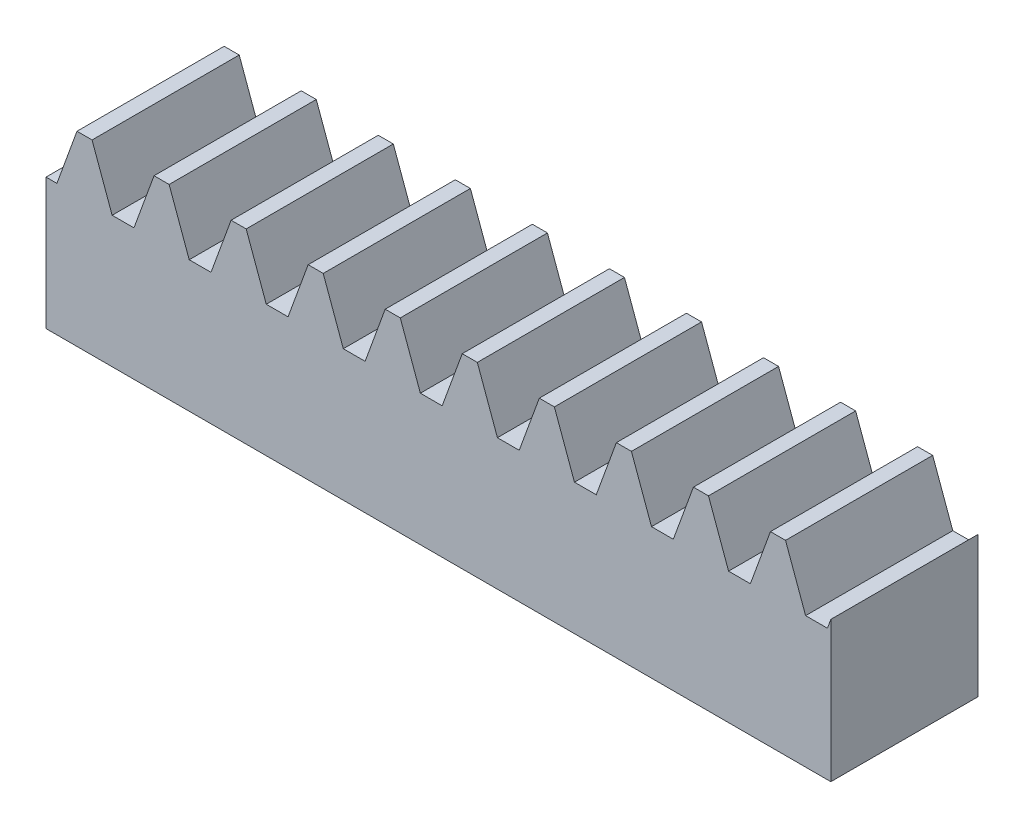
SolidWorks part; units mm, degrees
extrude "Blank" add sketch "BlankSke" against normal blind 3
sketch "BlankSke" plane through (0, 0, 0) normal (0, 0, 1) x (1, 0, 0)
  line L1 (0, 0) -> (16, 0)
  line L2 (0, 0) -> (0, 3.8)
  line L3 (0, 3.8) -> (16, 3.8)
  line L4 (16, 0) -> (16, 3.8)
  dimension "Length" = 16
  dimension "Blank_height" = 3.8
ref_plane "Plane1" through (0, 0, 0) normal (0, 0, 1) x (1, 0, 0)
ref_plane "Plane2" through (0, 0, 0) normal (0, 1, 0) x (1, 0, 0)
ref_plane "Plane3" through (0, 0, 0) normal (1, 0, 0) x (0, 0, -1)
other "Configuration Table"
sketch "HoldingSke" plane through (0, 0, 0) normal (0, 1, 0) x (1, 0, 0)
  line L0 (0, 0) -> (0.2783, 1.9805)
  line L1 (-15, 0) -> (100, 0) construction
  line L2 (0, 0) -> (-2.1039, 2.3779)
  line L3 (0, 0) -> (-11.863, 4.5341)
  line L4 (0, 0) -> (8.4473, 1.7955)
  line L5 (0, 0) -> (-23.7986, -8.8762)
  line L6 (0, 0) -> (-10.5278, -7.1032)
  line L9 (-71.009, 38.7566) -> (-55.9739, 44.2289)
  line L10 (-76.2, 2.8779) -> (-72.4, 2.8779)
  line L11 (0, 0) -> (-3, 0)
  line L12 (-76.2, 101.6) -> (-76.181, 101.6)
  line L13 (24.9733, 27.94) -> (52.9518, 28.4284)
  line L14 (24.9733, 27.94) -> (24.9743, 27.94)
  line L15 (24.9733, 27.94) -> (100.4006, 29.5858)
  circle A0 centre (0, 0) radius 19.05
  circle A1 centre (0, 0) radius 1.9
  circle A2 centre (0, 0) radius 12.7
  dimension "MPH" = 3.8
  dimension "Diameter" = 38.1
  dimension "Num_teeth" = 12
  dimension "Pitch" = 2
  dimension "Show_teeth" = 998
  dimension "Thickness" = 12.7
  dimension "Ap" = 20
  dimension "Pitch_height" = 3.8
  dimension "Width" = 3
  dimension "Backlash" = 0.019
  dimension "Addendum_fac" = 1
  dimension "Dedendum_fac" = 1.25
  dimension "Clearance_fac" = 0.25
  dimension "Dedendum_add" = 0.001
  dimension "Length" = 16
  dimension "Module" = 0.5
sketch "TooCutSkeIll" plane through (0, 0, 0) normal (0, 0, 1) x (1, 0, 0)
  line L0 (-0.4449, 3.7868) -> (-0.2524, 3.2579)
  line L1 (-0.134, 3.175) -> (0.134, 3.175)
  line L2 (0.2524, 3.2579) -> (0.4449, 3.7868)
  line L3 (16, 3.8) -> (0, 3.8) construction
  line L4 (0, 0) -> (0, 64.897) construction
  line L5 (-13.208, 3.8) -> (12.954, 3.8) construction
  line L6 (0, 0) -> (16, 0) construction
  line L7 (0.4497, 3.8) -> (0.4497, 48.7463) construction
  line L8 (-0.4497, 3.8) -> (-0.4497, 48.7463) construction
  line L9 (0.4637, 3.8) -> (0.4637, 4.3254)
  line L10 (-0.4637, 3.8) -> (-0.4637, 4.3254)
  line L11 (-0.4637, 4.3254) -> (0.4637, 4.3254)
  arc A0 (0.134, 3.175) -> (0.2524, 3.2579) centre (0.134, 3.301) ccw
  arc A1 (-0.2524, 3.2579) -> (-0.134, 3.175) centre (-0.134, 3.301) ccw
  arc A2 (0.4637, 3.8) -> (0.4449, 3.7868) centre (0.4637, 3.78) ccw
  arc A3 (-0.4449, 3.7868) -> (-0.4637, 3.8) centre (-0.4637, 3.78) ccw
  dimension "Pitch_height" = 3.8
  dimension "Addendum_plus" = 0.5254
  dimension "Pressure_angle" = 20
  dimension "Gap_width" = 0.8994
  dimension "Dedendum" = 0.625
extrude "ToothCutIll" [suppressed] cut sketch "TooCutSkeIll" against normal through all
sketch "TooCutSkeSim" plane through (0, 0, 0) normal (0, 0, 1) x (1, 0, 0)
  line L0 (0.2222, 2.675) -> (-0.2222, 2.675)
  line L1 (0.6409, 3.8254) -> (0.2222, 2.675)
  line L2 (0, 17.4625) -> (0, 53.467) construction
  line L3 (0.6409, 3.8254) -> (-0.6409, 3.8254)
  line L6 (-0.6409, 3.8254) -> (-0.2222, 2.675)
  line L9 (-0.4497, 3.3) -> (0.4497, 3.3) construction
  line L10 (0, 0) -> (16, 0) construction
  line L11 (0.4497, 3.3) -> (0.4497, 53.467) construction
  line L12 (-0.4497, 3.3) -> (-0.4497, 53.467) construction
  dimension "Addendum_plus" = 0.5254
  dimension "Pitch_height" = 3.3
  dimension "Pressure_angle" = 20
  dimension "Gap_width" = 0.8994
  dimension "Dedendum" = 0.625
extrude "ToothCutSim" cut sketch "TooCutSkeSim" against normal through all
pattern_linear "TeethCuts" count 11 spacing 1.5708 along (1, 0, 0) of "ToothCutIll", "ToothCutSim"
equation "' \"Module@HoldingSke\" = 6.35"
equation "' \"Num_teeth@HoldingSke\" = 12"
equation "' \"Ap@HoldingSke\" =  20"
equation "' \"Ap@HoldingSke\" = 20"
equation "' \"Width@HoldingSke\" = 0.25 * 25.4"
equation "' \"Show_teeth@HoldingSke\" = 500"
equation "' \"Backlash@HoldingSke\" = 0.009 * 25.4"
equation "' \"Addendum_fac@HoldingSke\" = 1.0"
equation "' \"Dedendum_fac@HoldingSke\" = 1.25"
equation "' \"Dedendum_add@HoldingSke\" = 0.00005 * 25.4"
equation "' \"Clearance_fac@HoldingSke\" = 0.25"
equation "' \"Pitch_height@HoldingSke\" = 1 * 25.4"
equation "' \"Length@HoldingSke\" = 4.71 * 25.4"
equation "\"Pitch@HoldingSke\" = 1 / \"Module@HoldingSke\""
equation "\"MPH@HoldingSke\" = \"Dedendum_fac@HoldingSke\" / \"Pitch@HoldingSke\" + 2 * \"Dedendum_add@HoldingSke\" + 0.002 * 25.4"
equation "\"MPH@HoldingSke\" = ((sgn( \"MPH@HoldingSke\" - \"Pitch_height@HoldingSke\")+1)*( \"MPH@HoldingSke\" - \"Pitch_height@HoldingSke\"))/2 + \"Pitch_height@HoldingSke\""
equation "\"Length@BlankSke\" =  \"Length@HoldingSke\""
equation "\"Face_width@Blank\" = \"Width@HoldingSke\""
equation "\"Pressure_angle@TooCutSkeIll\" = \"Ap@HoldingSke\""
equation "\"Addendum_plus@TooCutSkeIll\" =  \"Addendum_fac@HoldingSke\"  / \"Pitch@HoldingSke\" + 0.001 *25.4"
equation "\"Dedendum@TooCutSkeIll\" = \"Dedendum_fac@HoldingSke\"  / \"Pitch@HoldingSke\""
equation "\"Pitch_height@TooCutSkeIll\" =  \"MPH@HoldingSke\""
equation "\"Gap_width@TooCutSkeIll\" = 3.14159265 / 2 / \"Pitch@HoldingSke\" + 6 * \"Backlash@HoldingSke\""
equation "\"Pressure_angle@TooCutSkeSim\" = \"Ap@HoldingSke\""
equation "\"Addendum_plus@TooCutSkeSim\" =  \"Addendum_fac@HoldingSke\"  / \"Pitch@HoldingSke\" + 0.001 * 25.4"
equation "\"Dedendum@TooCutSkeSim\" = \"Dedendum_fac@HoldingSke\"  / \"Pitch@HoldingSke\""
equation "\"Gap_width@TooCutSkeSim\" = 3.14159265 / 2 / \"Pitch@HoldingSke\" + 6 * \"Backlash@HoldingSke\""
equation "\"Root_fillet@TooCutSkeIll\" = \"Clearance_fac@HoldingSke\" / \"Pitch@HoldingSke\" + \"Dedendum_add@HoldingSke\""
equation "\"Break_rad@TooCutSkeIll\" = 0.02 / \"Pitch@HoldingSke\" * 2"
equation "\"Linear_pitch@TeethCuts\" = 3.14159265 / \"Pitch@HoldingSke\""
equation "\"Num_teeth@HoldingSke\" = int( ( \"Length@HoldingSke\" + 0 ) / (3.14159265 / \"Pitch@HoldingSke\")) + 0.9999  + 1"
equation " \"Num_teeth@TeethCuts\" = int( \"Show_teeth@HoldingSke\" ) + 1"
equation " \"Num_teeth@TeethCuts\" = ((sgn( \"Num_teeth@TeethCuts\" - \"Num_teeth@HoldingSke\" )-1)*( \"Num_teeth@TeethCuts\" - \"Num_teeth@HoldingSke\" ))/-2+ \"Num_teeth@HoldingSke\""
equation " \"Num_teeth@TeethCuts\" = ((sgn( \"Num_teeth@TeethCuts\" - 2.0)+1)*( \"Num_teeth@TeethCuts\" - 2.0))/2 +2.0"
